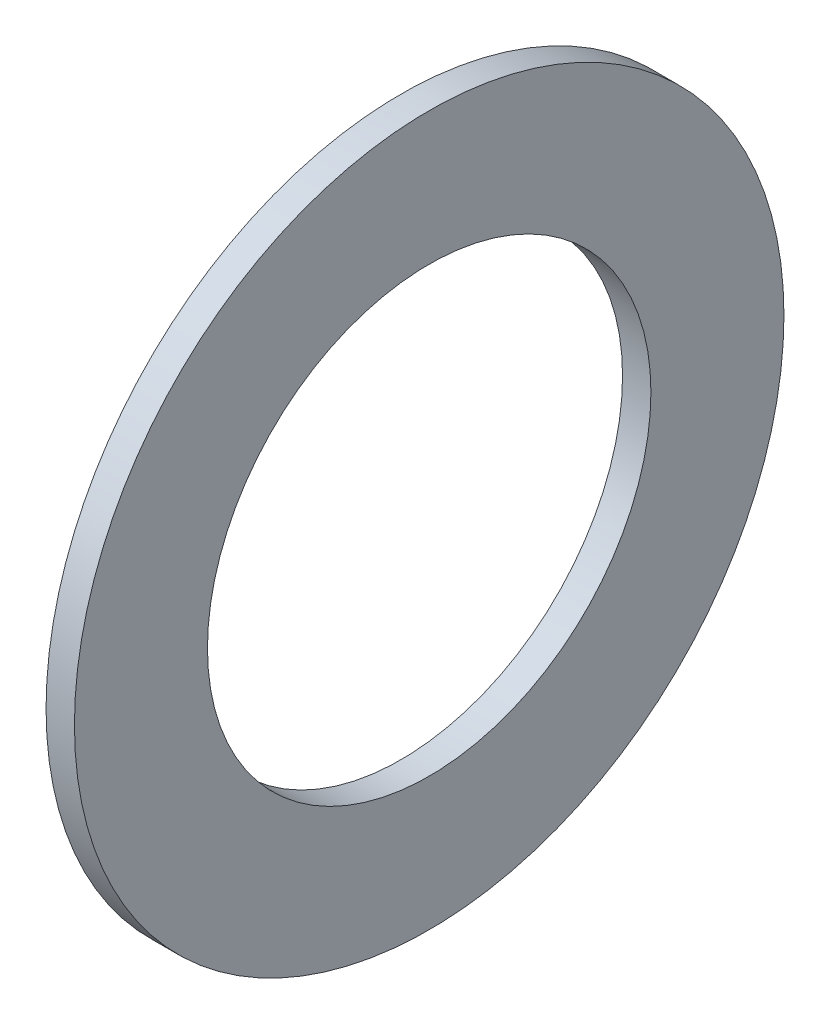
SolidWorks part; units mm, degrees
material "PTFE (general)"
ref_plane "Front Plane" through (0, 0, 0) normal (0, 0, 1) x (1, 0, 0)
ref_plane "Top Plane" through (0, 0, 0) normal (0, 1, 0) x (1, 0, 0)
ref_plane "Right Plane" through (0, 0, 0) normal (1, 0, 0) x (0, 0, -1)
sketch "Sketch1" plane through (0, 0, 0) normal (1, 0, 0) x (0, 0, -1)
  circle A0 centre (0, 0) radius 3.9688
  circle A1 centre (0, 0) radius 6.35
  dimension "D1" = 7.9375
  dimension "D2" = 12.7
extrude "Boss-Extrude1" add sketch "Sketch1" along normal blind 0.508
